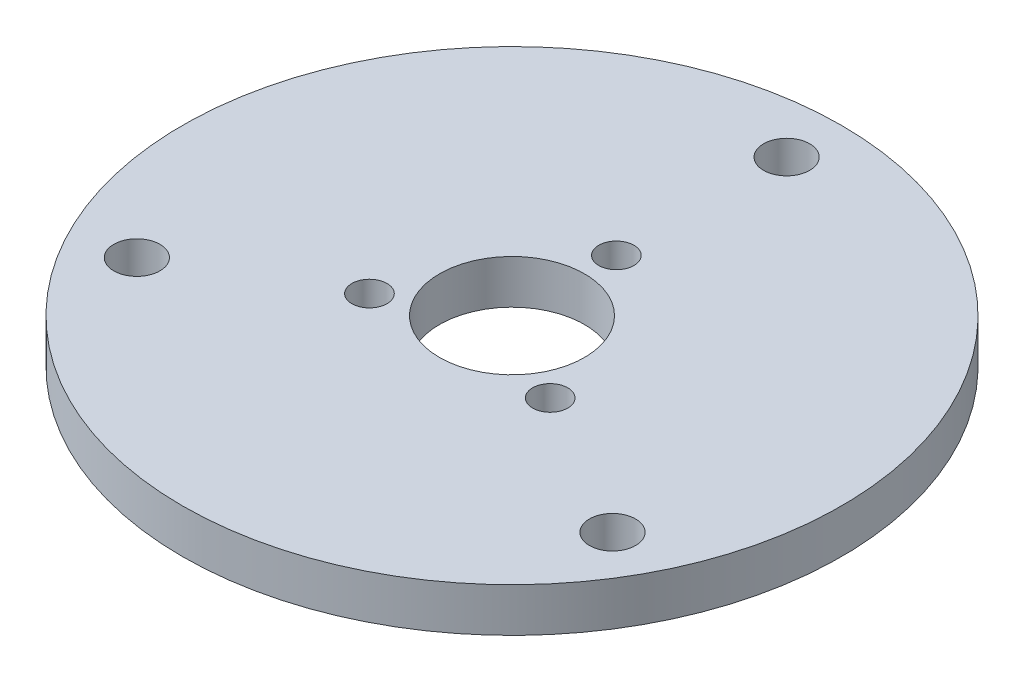
SolidWorks part; units mm, degrees
material "1060 合金"
ref_plane "前视基准面" through (0, 0, 0) normal (0, 0, 1) x (1, 0, 0)
ref_plane "上视基准面" through (0, 0, 0) normal (0, 1, 0) x (1, 0, 0)
ref_plane "右视基准面" through (0, 0, 0) normal (1, 0, 0) x (0, 0, -1)
sketch "草图1" plane through (0, 0, 0) normal (0, 1, 0) x (1, 0, 0)
  circle A0 centre (0, 0) radius 30
  dimension "D1" = 60
extrude "凸台-拉伸1" add sketch "草图1" along normal blind 4
sketch "草图2" plane through (0, 4, 0) normal (0, 1, 0) x (1, 0, 0)
  circle A0 centre (0, 0) radius 25
  circle A1 centre (0, 25) radius 2.1
  dimension "D1" = 50
  dimension "D2" = 4.2
extrude "切除-拉伸1" cut sketch "草图2" against normal blind 4 contours A0 A1 | A0 A1
pattern_circular "阵列(圆周)1" count 3 over 360 about axis through (0, 0, 0) along (0, 1, 0) of "切除-拉伸1"
sketch "草图3" plane through (0, 4, 0) normal (0, 1, 0) x (1, 0, 0)
  circle A0 centre (0, 0) radius 6.6
  dimension "D1" = 13.2
extrude "切除-拉伸2" cut sketch "草图3" against normal blind 17
sketch "草图4" plane through (0, 4, 0) normal (0, 1, 0) x (1, 0, 0)
  line L0 (0, 0) -> (21.6506, -12.5)
  circle A0 centre (0, 0) radius 9.5
  circle A1 centre (8.2272, -4.75) radius 1.6
  dimension "D1" = 19
  dimension "D2" = 3.2
  dimension "D3" = 0
extrude "切除-拉伸3" cut sketch "草图4" against normal blind 17 contours A0 A1 | A0 A1
pattern_circular "阵列(圆周)2" count 3 over 360 about axis through (0, 0, 0) along (0, 1, 0) of "切除-拉伸3"
